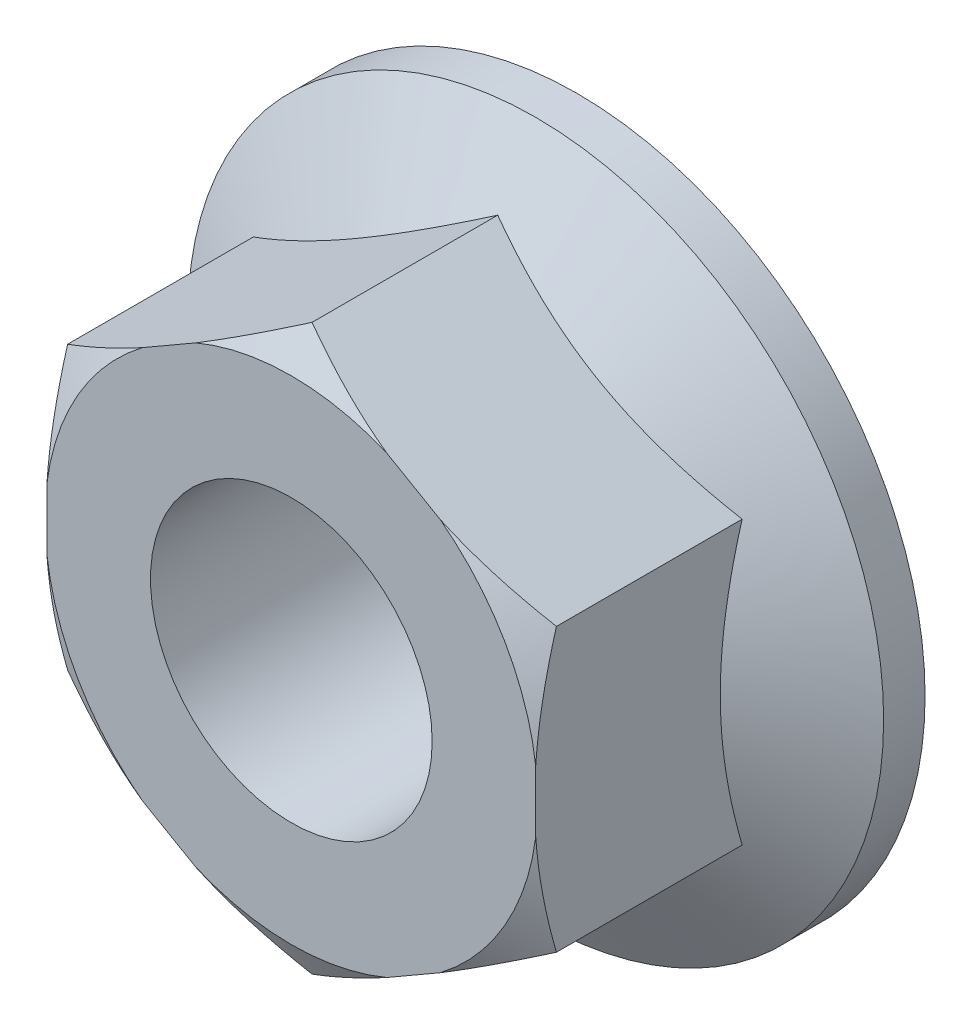
SolidWorks part; units mm, degrees
material "Acier allié"
ref_plane "Plan de face" through (0, 0, 0) normal (0, 0, 1) x (1, 0, 0)
ref_plane "Plan de dessus" through (0, 0, 0) normal (0, 1, 0) x (1, 0, 0)
ref_plane "Plan de droite" through (0, 0, 0) normal (1, 0, 0) x (0, 0, -1)
sketch "Esquisse1" plane through (0, 0, 0) normal (0, 0, 1) x (1, 0, 0)
  line L1 (-5.9, -3.4064) -> (0, -6.8127)
  line L2 (0, -6.8127) -> (5.9, -3.4064)
  line L3 (5.9, -3.4064) -> (5.9, 3.4064)
  line L4 (5.9, 3.4064) -> (0, 6.8127)
  line L5 (0, 6.8127) -> (-5.9, 3.4064)
  line L6 (-5.9, 3.4064) -> (-5.9, -3.4064)
  circle A0 centre (0, 0) radius 5.9 construction
  dimension "D1" = 11.8
extrude "Boss.-Extru.1" add sketch "Esquisse1" along normal blind 6.9
sketch "Esquisse2" plane through (0, 0, 0) normal (1, 0, 0) x (0, 0, -1)
  line L0 (0, 0) -> (-9.1826, 0) construction
  line L1 (-1, 8.4) -> (-2.5, 5.8019)
  line L2 (0, 0) -> (-2.5, 0)
  line L3 (0, 0) -> (0, 8.4)
  line L4 (0, 8.4) -> (-1, 8.4)
  line L5 (-2.5, 0) -> (-2.5, 5.8019)
  line L6 (-6.9, -3.4064) -> (-6.9, 3.4064) construction
  dimension "D1" = 16.8
  dimension "D2" = 4.4
  dimension "D3" = 1
  dimension "D4" = 30
revolve "Révolution1" add sketch "Esquisse2" angle 360 about L0
sketch "Esquisse3" plane through (0, 0, 0) normal (1, 0, 0) x (0, 0, -1)
  line L0 (0, 0) -> (-8.8054, 0) construction
  line L1 (-6.9, 6.8127) -> (-6.9, 5.9467)
  line L2 (-6.9, 5.9467) -> (-6.4, 6.8127)
  line L3 (-6.9, 6.8127) -> (-6.4, 6.8127)
  dimension "D1" = 0.5
  dimension "D2" = 30
revolve "Enlèvement de matière-Révolution1" cut sketch "Esquisse3" angle 360 about L0
hole_wizard "Trou taraudé M81" positions "Esquisse5" profile "Esquisse4" tap size "M8" standard "ISO" end condition through all
sketch "Esquisse5" plane through (0, 0, 6.9) normal (0, 0, 1) x (1, 0, 0)
  point P0 (0, 0)
sketch "Esquisse4" plane through (0, 0, 6.9) normal (1, 0, 0) x (0, -1, 0)
  line L0 (0, 0) -> (0, 6.9)
  line L1 (0, 6.9) -> (3.4, 6.9)
  line L2 (3.4, 6.9) -> (3.4, 0)
  line L5 (3.4, 0) -> (0, 0)
  line L11 (0, -6.35) -> (0, 107.95) construction
  dimension "Diamètre du trou pour taraudage jusqu'au prochain" = 6.8
  dimension "Profondeur du trou pour taraudage jusqu'au prochain" = 6.9
cosmetic thread "Filetage de perçage1" parameters "D2"=8
